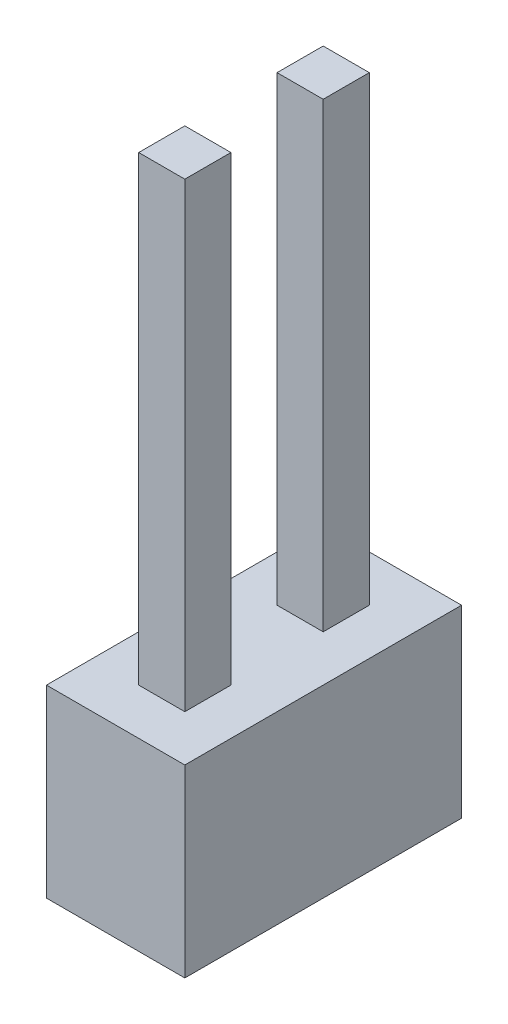
SolidWorks part; units mm, degrees
ref_plane "Front Plane" through (0, 0, 0) normal (0, 0, 1) x (1, 0, 0)
ref_plane "Top Plane" through (0, 0, 0) normal (0, 1, 0) x (1, 0, 0)
ref_plane "Right Plane" through (0, 0, 0) normal (1, 0, 0) x (0, 0, -1)
sketch "Sketch1" plane through (0, 0, 0) normal (0, 1, 0) x (1, 0, 0)
  line L1 (0, 0) -> (2.286, 0)
  line L2 (0, 0) -> (0, 4.572)
  line L3 (0, 4.572) -> (2.286, 4.572)
  line L4 (2.286, 0) -> (2.286, 4.572)
  dimension "D1" = 2.286
  dimension "D2" = 4.572
extrude "Extrude1" add sketch "Sketch1" along normal blind 3.048
sketch "Sketch2" plane through (0, 3.048, 0) normal (0, 1, 0) x (1, 0, 0)
  line L0 (0, 4.572) -> (0, 0) construction
  line L1 (0.762, 0.762) -> (1.524, 0.762)
  line L2 (0.762, 0.762) -> (0.762, 1.524)
  line L3 (0.762, 1.524) -> (1.524, 1.524)
  line L4 (1.524, 0.762) -> (1.524, 1.524)
  line L5 (0.762, 3.048) -> (1.524, 3.048)
  line L6 (0.762, 3.048) -> (0.762, 3.81)
  line L7 (0.762, 3.81) -> (1.524, 3.81)
  line L8 (1.524, 3.048) -> (1.524, 3.81)
  line L9 (0, 0) -> (2.286, 0) construction
  line L10 (2.286, 4.572) -> (0, 4.572) construction
  dimension "D1" = 0.762
  dimension "D2" = 0.762
  dimension "D3" = 0.762
  dimension "D4" = 0.762
  dimension "D5" = 0.762
  dimension "D6" = 0.762
  dimension "D7" = 0.762
  dimension "D8" = 0.762
extrude "Extrude2" add sketch "Sketch2" along normal blind 7.62
